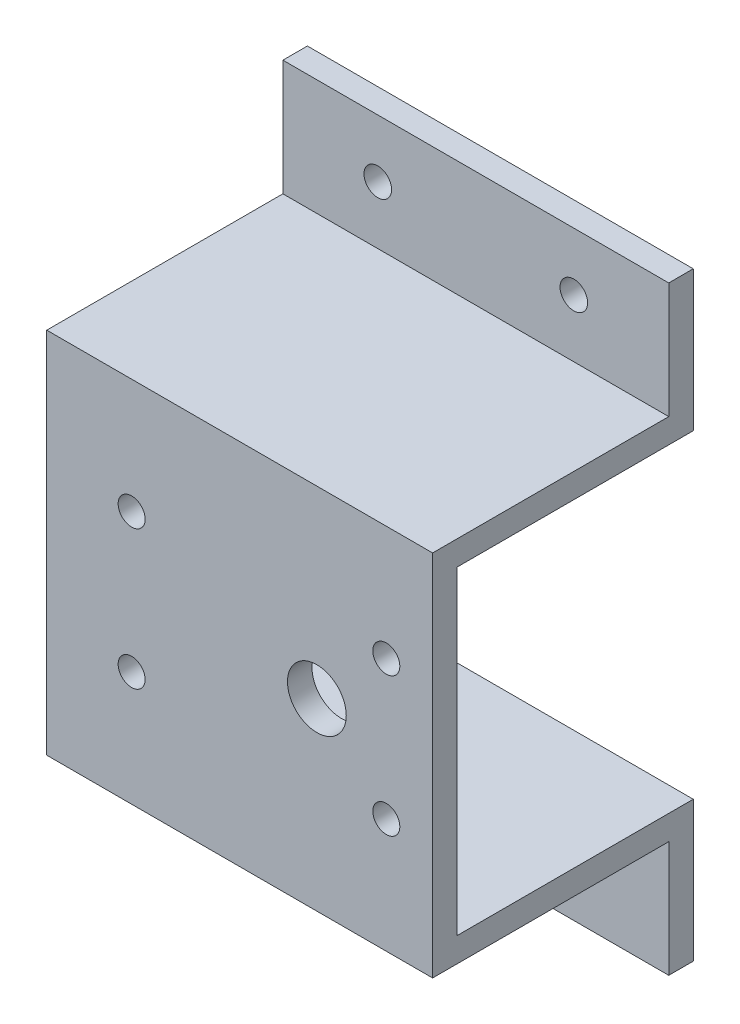
SolidWorks part; units mm, degrees
ref_plane "Front Plane" through (0, 0, 0) normal (0, 0, 1) x (1, 0, 0)
ref_plane "Top Plane" through (0, 0, 0) normal (0, 1, 0) x (1, 0, 0)
ref_plane "Right Plane" through (0, 0, 0) normal (1, 0, 0) x (0, 0, -1)
sketch "Sketch1" plane through (0, 0, 0) normal (0, 0, 1) x (1, 0, 0)
  line L0 (0, 0) -> (15, 0) construction
  line L1 (15, 23.85) -> (-35, 23.85)
  line L2 (15, 23.85) -> (15, -23.85)
  line L3 (15, -23.85) -> (-35, -23.85)
  line L4 (-35, 23.85) -> (-35, -23.85)
  circle A1 centre (-24, 9) radius 1.75
  circle A2 centre (-24, -9) radius 1.75
  circle A3 centre (9, -9) radius 1.75
  circle A4 centre (9, 9) radius 1.75
  circle A5 centre (0, 0) radius 3.81
  circle B0 centre (-24, -9) radius 3.5
  circle B1 centre (9, 9) radius 3.5
  circle B2 centre (0, 0) radius 6.25
  circle B3 centre (9, -9) radius 3.5
  circle B4 centre (-24, 9) radius 3.5
  dimension "D1" = 3.5
  dimension "D2" = 7.62
  dimension "D3" = 9
  dimension "D4" = 23.85
  dimension "D5" = 50
  dimension "D6" = 15
sketch_block_instance "Little_Motor_Screw_Holes-1"
sketch_block "Little_Motor_Screw_Holes"
extrude "Boss-Extrude1" add sketch "Sketch1" along normal blind 3.175
sketch "Sketch2" plane through (0, 0, 0) normal (0, 0, -1) x (-1, 0, 0)
  line L0 (35, -23.85) -> (-15, -23.85)
  line L1 (35, -23.85) -> (35, -20.675)
  line L2 (-15, -23.85) -> (-15, -20.675)
  line L3 (35, -20.675) -> (-15, -20.675)
  line L4 (-15, 23.85) -> (35, 23.85)
  line L5 (-15, 23.85) -> (-15, 20.675)
  line L6 (35, 23.85) -> (35, 20.675)
  line L7 (-15, 20.675) -> (35, 20.675)
  dimension "D1" = 3.175
  dimension "D2" = 3.175
extrude "Boss-Extrude2" add sketch "Sketch2" along normal blind 30.5976
sketch "Sketch3" plane through (0, 23.85, 0) normal (0, 1, 0) x (1, 0, 0)
  line L0 (-35, 30.5976) -> (15, 30.5976)
  line L1 (-35, 30.5976) -> (-35, 27.4226)
  line L2 (15, 30.5976) -> (15, 27.4226)
  line L3 (-35, 27.4226) -> (15, 27.4226)
  dimension "D1" = 3.175
extrude "Boss-Extrude3" add sketch "Sketch3" along normal blind 15
sketch "Sketch4" plane through (0, 0, -27.4226) normal (0, 0, 1) x (1, 0, 0)
  line L0 (-22.7, 31.35) -> (-35, 31.35) construction
  line L1 (-35, 38.85) -> (-35, 23.85) construction
  line L2 (-22.7, 31.35) -> (2.7, 31.35) construction
  line L3 (2.7, 31.35) -> (15, 31.35) construction
  line L4 (15, 38.85) -> (15, 23.85) construction
  circle A0 centre (2.7, 31.35) radius 1.7859
  circle A1 centre (-22.7, 31.35) radius 1.7859
  dimension "D1" = 3.5719
  dimension "D2" = 25.4
extrude "Cut-Extrude1" cut sketch "Sketch4" against normal up to next
mirror "Mirror1" about plane through (0, 0, 0) normal (0, 1, 0) of "Cut-Extrude1", "Boss-Extrude3"
